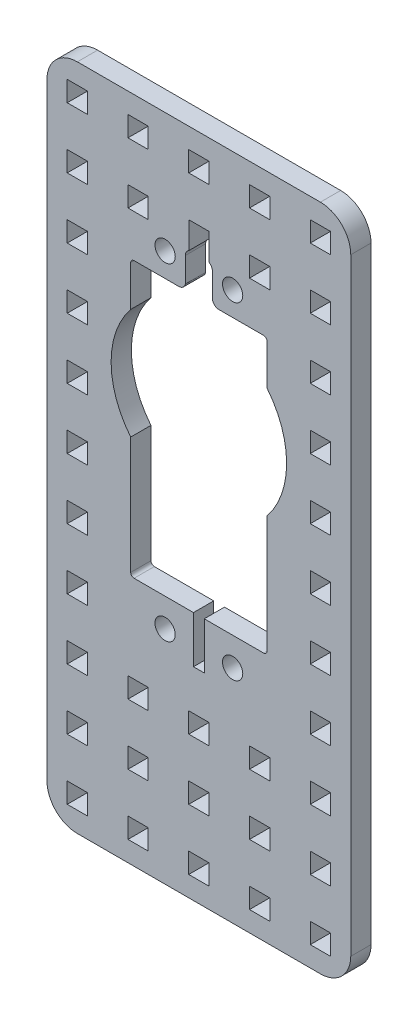
SolidWorks part; units mm, degrees
ref_plane "Alzado" through (0, 0, 0) normal (0, 0, 1) x (1, 0, 0)
ref_plane "Planta" through (0, 0, 0) normal (0, 1, 0) x (1, 0, 0)
ref_plane "Vista lateral" through (0, 0, 0) normal (1, 0, 0) x (0, 0, -1)
sketch "Model" plane through (0, 0, 0) normal (0, 0, 1) x (1, 0, 0)
  line L0 (54.856, 289.902) -> (51.856, 289.902)
  line L1 (54.856, 286.902) -> (54.856, 289.902)
  line L2 (51.856, 286.902) -> (54.856, 286.902)
  line L3 (51.856, 289.902) -> (51.856, 286.902)
  line L4 (54.856, 280.902) -> (51.856, 280.902)
  line L5 (54.856, 277.902) -> (54.856, 280.902)
  line L6 (51.856, 277.902) -> (54.856, 277.902)
  line L7 (51.856, 280.902) -> (51.856, 277.902)
  line L8 (54.856, 271.902) -> (51.856, 271.902)
  line L9 (54.856, 268.902) -> (54.856, 271.902)
  line L10 (51.856, 268.902) -> (54.856, 268.902)
  line L11 (51.856, 271.902) -> (51.856, 268.902)
  line L12 (54.856, 262.902) -> (51.856, 262.902)
  line L13 (54.856, 259.902) -> (54.856, 262.902)
  line L14 (51.856, 259.902) -> (54.856, 259.902)
  line L15 (51.856, 262.902) -> (51.856, 259.902)
  line L16 (54.856, 253.902) -> (51.856, 253.902)
  line L17 (54.856, 250.902) -> (54.856, 253.902)
  line L18 (51.856, 250.902) -> (54.856, 250.902)
  line L19 (51.856, 253.902) -> (51.856, 250.902)
  line L20 (54.856, 244.902) -> (51.856, 244.902)
  line L21 (54.856, 241.902) -> (54.856, 244.902)
  line L22 (51.856, 241.902) -> (54.856, 241.902)
  line L23 (51.856, 244.902) -> (51.856, 241.902)
  line L24 (54.856, 235.902) -> (51.856, 235.902)
  line L25 (54.856, 232.902) -> (54.856, 235.902)
  line L26 (51.856, 232.902) -> (54.856, 232.902)
  line L27 (51.856, 235.902) -> (51.856, 232.902)
  line L28 (54.856, 226.902) -> (51.856, 226.902)
  line L29 (54.856, 223.902) -> (54.856, 226.902)
  line L30 (51.856, 223.902) -> (54.856, 223.902)
  line L31 (51.856, 226.902) -> (51.856, 223.902)
  line L32 (54.856, 217.902) -> (51.856, 217.902)
  line L33 (54.856, 214.902) -> (54.856, 217.902)
  line L34 (51.856, 214.902) -> (54.856, 214.902)
  line L35 (51.856, 217.902) -> (51.856, 214.902)
  line L36 (54.856, 208.902) -> (51.856, 208.902)
  line L37 (54.856, 205.902) -> (54.856, 208.902)
  line L38 (51.856, 205.902) -> (54.856, 205.902)
  line L39 (51.856, 208.902) -> (51.856, 205.902)
  line L40 (54.856, 199.902) -> (51.856, 199.902)
  line L41 (54.856, 196.902) -> (54.856, 199.902)
  line L42 (51.856, 196.902) -> (54.856, 196.902)
  line L43 (51.856, 199.902) -> (51.856, 196.902)
  line L44 (18.856, 289.902) -> (15.856, 289.902)
  line L45 (18.856, 286.902) -> (18.856, 289.902)
  line L46 (15.856, 286.902) -> (18.856, 286.902)
  line L47 (15.856, 289.902) -> (15.856, 286.902)
  line L48 (18.856, 280.902) -> (15.856, 280.902)
  line L49 (18.856, 277.902) -> (18.856, 280.902)
  line L50 (15.856, 277.902) -> (18.856, 277.902)
  line L51 (15.856, 280.902) -> (15.856, 277.902)
  line L52 (18.856, 271.902) -> (15.856, 271.902)
  line L53 (18.856, 268.902) -> (18.856, 271.902)
  line L54 (15.856, 268.902) -> (18.856, 268.902)
  line L55 (15.856, 271.902) -> (15.856, 268.902)
  line L56 (18.856, 262.902) -> (15.856, 262.902)
  line L57 (18.856, 259.902) -> (18.856, 262.902)
  line L58 (15.856, 259.902) -> (18.856, 259.902)
  line L59 (15.856, 262.902) -> (15.856, 259.902)
  line L60 (18.856, 253.902) -> (15.856, 253.902)
  line L61 (18.856, 250.902) -> (18.856, 253.902)
  line L62 (15.856, 250.902) -> (18.856, 250.902)
  line L63 (15.856, 253.902) -> (15.856, 250.902)
  line L64 (18.856, 244.902) -> (15.856, 244.902)
  line L65 (18.856, 241.902) -> (18.856, 244.902)
  line L66 (15.856, 241.902) -> (18.856, 241.902)
  line L67 (15.856, 244.902) -> (15.856, 241.902)
  line L68 (18.856, 235.902) -> (15.856, 235.902)
  line L69 (18.856, 232.902) -> (18.856, 235.902)
  line L70 (15.856, 232.902) -> (18.856, 232.902)
  line L71 (15.856, 235.902) -> (15.856, 232.902)
  line L72 (18.856, 226.902) -> (15.856, 226.902)
  line L73 (18.856, 223.902) -> (18.856, 226.902)
  line L74 (15.856, 223.902) -> (18.856, 223.902)
  line L75 (15.856, 226.902) -> (15.856, 223.902)
  line L76 (18.856, 217.902) -> (15.856, 217.902)
  line L77 (18.856, 214.902) -> (18.856, 217.902)
  line L78 (15.856, 214.902) -> (18.856, 214.902)
  line L79 (15.856, 217.902) -> (15.856, 214.902)
  line L80 (18.856, 208.902) -> (15.856, 208.902)
  line L81 (18.856, 205.902) -> (18.856, 208.902)
  line L82 (15.856, 205.902) -> (18.856, 205.902)
  line L83 (15.856, 208.902) -> (15.856, 205.902)
  line L84 (18.856, 199.902) -> (15.856, 199.902)
  line L85 (18.856, 196.902) -> (18.856, 199.902)
  line L86 (15.856, 196.902) -> (18.856, 196.902)
  line L87 (15.856, 199.902) -> (15.856, 196.902)
  line L88 (45.856, 199.902) -> (42.856, 199.902)
  line L89 (45.856, 196.902) -> (45.856, 199.902)
  line L90 (42.856, 196.902) -> (45.856, 196.902)
  line L91 (42.856, 199.902) -> (42.856, 196.902)
  line L92 (27.856, 199.902) -> (24.856, 199.902)
  line L93 (27.856, 196.902) -> (27.856, 199.902)
  line L94 (24.856, 196.902) -> (27.856, 196.902)
  line L95 (24.856, 199.902) -> (24.856, 196.902)
  line L96 (36.856, 199.902) -> (33.856, 199.902)
  line L97 (36.856, 196.902) -> (36.856, 199.902)
  line L98 (33.856, 196.902) -> (36.856, 196.902)
  line L99 (33.856, 199.902) -> (33.856, 196.902)
  line L100 (45.856, 217.902) -> (42.856, 217.902)
  line L101 (45.856, 214.902) -> (45.856, 217.902)
  line L102 (42.856, 214.902) -> (45.856, 214.902)
  line L103 (42.856, 217.902) -> (42.856, 214.902)
  line L104 (27.856, 217.902) -> (24.856, 217.902)
  line L105 (27.856, 214.902) -> (27.856, 217.902)
  line L106 (24.856, 214.902) -> (27.856, 214.902)
  line L107 (24.856, 217.902) -> (24.856, 214.902)
  line L108 (36.856, 217.902) -> (33.856, 217.902)
  line L109 (36.856, 214.902) -> (36.856, 217.902)
  line L110 (33.856, 214.902) -> (36.856, 214.902)
  line L111 (33.856, 217.902) -> (33.856, 214.902)
  line L112 (45.856, 208.902) -> (42.856, 208.902)
  line L113 (45.856, 205.902) -> (45.856, 208.902)
  line L114 (42.856, 205.902) -> (45.856, 205.902)
  line L115 (42.856, 208.902) -> (42.856, 205.902)
  line L116 (27.856, 208.902) -> (24.856, 208.902)
  line L117 (27.856, 205.902) -> (27.856, 208.902)
  line L118 (24.856, 205.902) -> (27.856, 205.902)
  line L119 (24.856, 208.902) -> (24.856, 205.902)
  line L120 (36.856, 208.902) -> (33.856, 208.902)
  line L121 (36.856, 205.902) -> (36.856, 208.902)
  line L122 (33.856, 205.902) -> (36.856, 205.902)
  line L123 (33.856, 208.902) -> (33.856, 205.902)
  line L124 (45.856, 289.902) -> (42.856, 289.902)
  line L125 (45.856, 286.902) -> (45.856, 289.902)
  line L126 (42.856, 286.902) -> (45.856, 286.902)
  line L127 (42.856, 289.902) -> (42.856, 286.902)
  line L128 (27.856, 289.902) -> (24.856, 289.902)
  line L129 (27.856, 286.902) -> (27.856, 289.902)
  line L130 (24.856, 286.902) -> (27.856, 286.902)
  line L131 (24.856, 289.902) -> (24.856, 286.902)
  line L132 (36.856, 289.902) -> (33.856, 289.902)
  line L133 (36.856, 286.902) -> (36.856, 289.902)
  line L134 (33.856, 286.902) -> (36.856, 286.902)
  line L135 (33.856, 289.902) -> (33.856, 286.902)
  line L136 (45.856, 280.902) -> (42.856, 280.902)
  line L137 (45.856, 277.902) -> (45.856, 280.902)
  line L138 (42.856, 277.902) -> (45.856, 277.902)
  line L139 (42.856, 280.902) -> (42.856, 277.902)
  line L140 (27.856, 280.902) -> (24.856, 280.902)
  line L141 (27.856, 277.902) -> (27.856, 280.902)
  line L142 (24.856, 277.902) -> (27.856, 277.902)
  line L143 (24.856, 280.902) -> (24.856, 277.902)
  line L144 (33.8579, 280.9016) -> (33.8579, 276.9317)
  line L145 (36.8579, 280.9016) -> (33.8579, 280.9016)
  line L146 (36.8579, 276.9317) -> (36.8579, 280.9016)
  line L147 (17.356, 193.902) -> (53.356, 193.902)
  line L148 (57.856, 198.402) -> (57.856, 288.402)
  line L149 (53.356, 292.902) -> (17.356, 292.902)
  line L150 (12.856, 288.402) -> (12.856, 198.402)
  line L151 (32.3781, 271.6016) -> (25.7579, 271.6016)
  line L152 (44.9579, 271.6016) -> (38.3377, 271.6016)
  line L153 (33.3579, 276.0657) -> (33.3579, 272.4016)
  line L154 (37.3579, 276.0657) -> (37.3579, 272.4016)
  line L157 (45.4576, 265.0847) -> (45.4578, 271.1016)
  line L158 (25.2578, 271.1025) -> (25.2576, 265.0889)
  line L159 (34.5557, 223.9021) -> (36.1557, 223.902)
  line L160 (34.556, 230.8521) -> (34.5557, 223.9021)
  line L161 (36.156, 230.852) -> (36.1557, 223.902)
  line L162 (25.756, 230.8525) -> (34.556, 230.8521)
  line L163 (45.4561, 231.3516) -> (45.4568, 248.7185)
  line L164 (25.2568, 248.7161) -> (25.2561, 231.3525)
  line L165 (36.156, 230.852) -> (44.956, 230.8516)
  arc A0 (53.356, 193.902) -> (57.856, 198.402) centre (53.356, 198.402) ccw
  arc A1 (12.856, 198.402) -> (17.356, 193.902) centre (17.356, 198.402) ccw
  arc A2 (57.856, 288.402) -> (53.356, 292.902) centre (53.356, 288.402) ccw
  arc A3 (17.356, 292.902) -> (12.856, 288.402) centre (17.356, 288.402) ccw
  arc A4 (32.3781, 271.6016) -> (33.3579, 272.4016) centre (32.3781, 272.6016) ccw
  arc A5 (37.3579, 272.4016) -> (38.3377, 271.6016) centre (38.3377, 272.6016) ccw
  arc A6 (33.8579, 276.9317) -> (33.3579, 276.0657) centre (34.3579, 276.0657) ccw
  arc A7 (37.3579, 276.0657) -> (36.8579, 276.9317) centre (36.3579, 276.0657) ccw
  arc A8 (45.4568, 248.7185) -> (45.4576, 265.0847) centre (35.3558, 256.902) ccw
  arc A9 (25.2576, 265.0889) -> (25.2568, 248.7161) centre (35.3558, 256.902) ccw
  arc A10 (45.4578, 271.1016) -> (44.9579, 271.6016) centre (44.9578, 271.1016) ccw
  arc A11 (44.956, 230.8516) -> (45.4561, 231.3516) centre (44.9561, 231.3516) ccw
  arc A12 (25.7579, 271.6016) -> (25.2578, 271.1025) centre (25.7578, 271.1016) ccw
  arc A13 (25.2561, 231.3525) -> (25.756, 230.8525) centre (25.7561, 231.3525) ccw
  circle A14 centre (40.3558, 226.6518) radius 1.5
  circle A15 centre (30.3558, 226.6523) radius 1.5
  circle A16 centre (40.358, 275.1518) radius 1.5
  circle A17 centre (30.358, 275.1523) radius 1.5
extrude "Saliente-Extruir1" add sketch "Model" along normal blind 3
